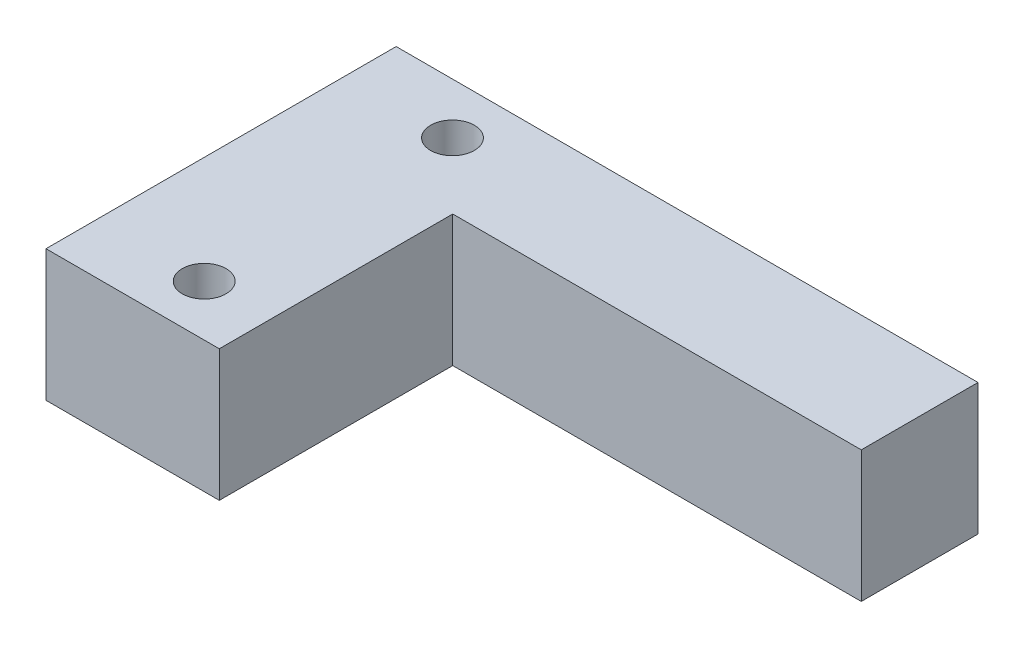
SolidWorks part; units mm, degrees
ref_plane "Front Plane" through (0, 0, 0) normal (0, 0, 1) x (1, 0, 0)
ref_plane "Top Plane" through (0, 0, 0) normal (0, 1, 0) x (1, 0, 0)
ref_plane "Right Plane" through (0, 0, 0) normal (1, 0, 0) x (0, 0, -1)
sketch "Sketch1" plane through (0, 0, 0) normal (0, 1, 0) x (1, 0, 0)
  line L1 (-19.939, -12) -> (19.939, -12)
  line L2 (-19.939, -12) -> (-19.939, 12)
  line L3 (-19.939, 12) -> (19.939, 12)
  line L4 (19.939, -12) -> (19.939, 12)
  circle A0 centre (-14.5292, -8.1486) radius 1.5
  circle A1 centre (-14.5292, 8.8694) radius 1.5
  point P4 (-19.939, 0)
  point P6 (0, -12)
  dimension "D4" = 3
  dimension "D1" = 39.878
  dimension "D2" = 24
  dimension "D3" = 17.018
extrude "Boss-Extrude1" add sketch "Sketch1" along normal blind 9 contours L3 L4 L1 L2
sketch "Sketch2" plane through (0, 9, 0) normal (0, 1, 0) x (1, 0, 0)
  line L0 (-19.939, -12) -> (19.939, -12) construction
  line L1 (-8.061, -12) -> (19.939, -12)
  line L2 (-8.061, -12) -> (-8.061, 4)
  line L3 (-8.061, 4) -> (19.939, 4)
  line L4 (19.939, -12) -> (19.939, 4)
  line L5 (19.939, -12) -> (19.939, 12) construction
  dimension "D1" = 28
  dimension "D2" = 16
extrude "Cut-Extrude1" cut sketch "Sketch2" against normal through all
sketch "Sketch4" plane through (0, 9, 0) normal (0, 1, 0) x (1, 0, 0)
  line L0 (-19.939, -12) -> (-19.939, 12) construction
  line L1 (-12.589, 8.509) -> (-12.589, -8.509) construction
  circle A0 centre (-12.589, -8.509) radius 1.5
  circle A1 centre (-12.589, 8.509) radius 1.5
  point P8 (-19.939, 0)
  point P9 (-12.589, 0)
  dimension "D2" = 3
  dimension "D1" = 17.018
  dimension "D3" = 7.35
extrude "Cut-Extrude2" cut sketch "Sketch4" against normal through all
